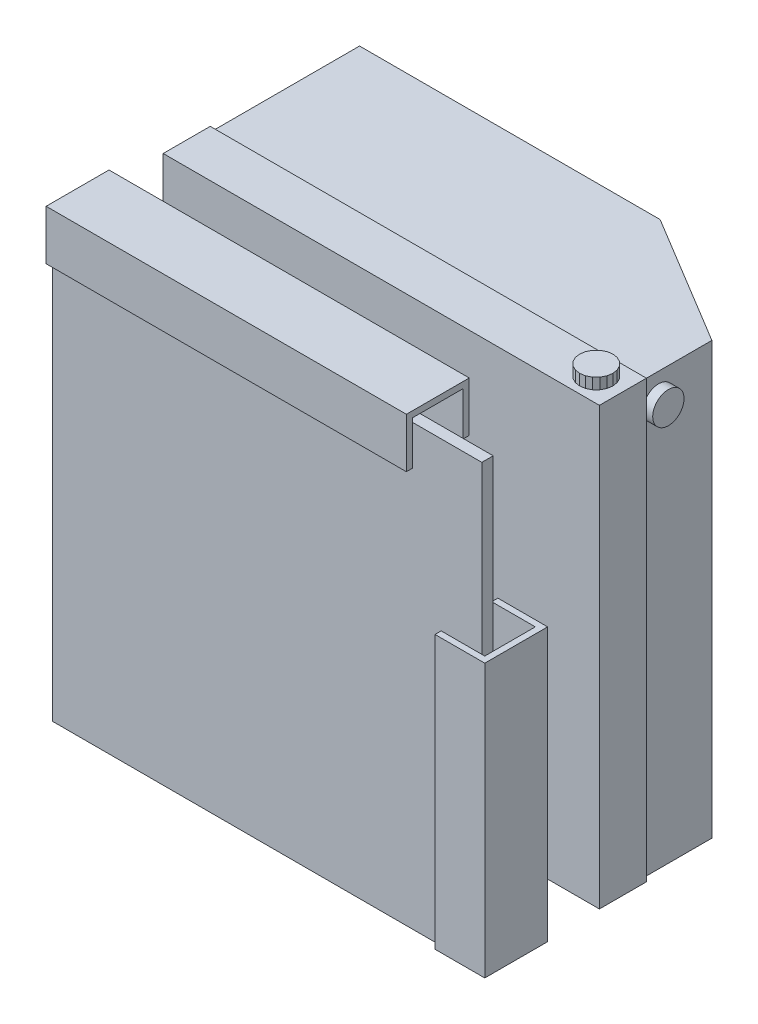
SolidWorks part; units mm, degrees
ref_plane "Front Plane" through (0, 0, 0) normal (0, 0, 1) x (1, 0, 0)
ref_plane "Top Plane" through (0, 0, 0) normal (0, 1, 0) x (1, 0, 0)
ref_plane "Right Plane" through (0, 0, 0) normal (1, 0, 0) x (0, 0, -1)
ref_plane "PY -55.000" through (0, -55, 0) normal (0, 1, 0) x (1, 0, 0)
sketch "housing sketch" plane through (0, -55, 0) normal (0, 1, 0) x (1, 0, 0)
  line L0 (0, 0) -> (0, 30)
  line L1 (0, 30) -> (-33.3047, 50.1)
  line L2 (-33.3047, 50.1) -> (-110, 50.1)
  line L3 (-110, 50.1) -> (-110, 0)
  line L4 (-110, 0) -> (0, 0)
extrude "housing" add sketch "housing sketch" along normal mid plane 110
ref_plane "PZ 26.850" through (0, 0, 26.85) normal (0, 0, 1) x (1, 0, 0)
sketch "diffuser sketch" plane through (0, 0, 26.85) normal (0, 0, 1) x (1, 0, 0)
  line L0 (-110, -110) -> (-0.4, -110)
  line L1 (-0.4, -110) -> (-0.4, 2)
  line L2 (-0.4, 2) -> (-110, 2)
  line L3 (-110, 2) -> (-110, -110)
extrude "diffuser" add sketch "diffuser sketch" along normal mid plane 2.9
ref_plane "PY -75.215" through (0, -75.215, 0) normal (0, 1, 0) x (1, 0, 0)
sketch "side channel sketch" plane through (0, -75.215, 0) normal (0, 1, 0) x (1, 0, 0)
  line L0 (-10.78, -13.83) -> (1.92, -13.83)
  line L1 (1.92, -13.83) -> (1.92, -29.87)
  line L2 (1.92, -29.87) -> (-10.78, -29.87)
  line L3 (-10.78, -29.87) -> (-10.78, -28.3)
  line L4 (-10.78, -28.3) -> (0.35, -28.3)
  line L5 (0.35, -28.3) -> (0.35, -15.4)
  line L6 (0.35, -15.4) -> (-10.78, -15.4)
  line L7 (-10.78, -15.4) -> (-10.78, -13.83)
extrude "side channel" add sketch "side channel sketch" along normal mid plane 69.57
ref_plane "PX -64.040" through (-64.04, 0, 0) normal (1, 0, 0) x (0, 0, -1)
sketch "end channel sketch" plane through (-64.04, 0, 0) normal (1, 0, 0) x (0, 0, -1)
  line L0 (-13.83, -8.13) -> (-13.83, 4.57)
  line L1 (-13.83, 4.57) -> (-29.87, 4.57)
  line L2 (-29.87, 4.57) -> (-29.87, -8.13)
  line L3 (-29.87, -8.13) -> (-28.3, -8.13)
  line L4 (-28.3, -8.13) -> (-28.3, 3)
  line L5 (-28.3, 3) -> (-15.4, 3)
  line L6 (-15.4, 3) -> (-15.4, -8.13)
  line L7 (-15.4, -8.13) -> (-13.83, -8.13)
extrude "end channel" add sketch "end channel sketch" along normal mid plane 91.92
ref_plane "PX 0.750" through (0.75, 0, 0) normal (1, 0, 0) x (0, 0, -1)
sketch "side screw head sketch" plane through (0.75, 0, 0) normal (1, 0, 0) x (0, 0, -1)
  circle A0 centre (16.4, -6.8) radius 4
extrude "side screw head" add sketch "side screw head sketch" along normal mid plane 3.5
ref_plane "PY -54.350" through (0, -54.35, 0) normal (0, 1, 0) x (1, 0, 0)
sketch "lens frame lap sketch" plane through (0, -54.35, 0) normal (0, 1, 0) x (1, 0, 0)
  line L0 (-110, 12) -> (1.3, 12)
  line L1 (1.3, 12) -> (1.3, 0)
  line L2 (1.3, 0) -> (-110, 0)
  line L3 (-110, 0) -> (-110, 12)
extrude "lens frame lap" add sketch "lens frame lap sketch" along normal mid plane 111.3
ref_plane "PY 1.550" through (0, 1.55, 0) normal (0, 1, 0) x (1, 0, 0)
sketch "corner screw head on the end sketch" plane through (0, 1.55, 0) normal (0, 1, 0) x (1, 0, 0)
  line L0 (-1.25, 6) -> (-1.458, 4.6867)
  line L1 (-1.458, 4.6867) -> (-2.0617, 3.5019)
  line L2 (-2.0617, 3.5019) -> (-3.0019, 2.5617)
  line L3 (-3.0019, 2.5617) -> (-4.1867, 1.958)
  line L4 (-4.1867, 1.958) -> (-5.5, 1.75)
  line L5 (-5.5, 1.75) -> (-6.8133, 1.958)
  line L6 (-6.8133, 1.958) -> (-7.9981, 2.5617)
  line L7 (-7.9981, 2.5617) -> (-8.9383, 3.5019)
  line L8 (-8.9383, 3.5019) -> (-9.542, 4.6867)
  line L9 (-9.542, 4.6867) -> (-9.75, 6)
  line L10 (-9.75, 6) -> (-9.542, 7.3133)
  line L11 (-9.542, 7.3133) -> (-8.9383, 8.4981)
  line L12 (-8.9383, 8.4981) -> (-7.9981, 9.4383)
  line L13 (-7.9981, 9.4383) -> (-6.8133, 10.042)
  line L14 (-6.8133, 10.042) -> (-5.5, 10.25)
  line L15 (-5.5, 10.25) -> (-4.1867, 10.042)
  line L16 (-4.1867, 10.042) -> (-3.0019, 9.4383)
  line L17 (-3.0019, 9.4383) -> (-2.0617, 8.4981)
  line L18 (-2.0617, 8.4981) -> (-1.458, 7.3133)
  line L19 (-1.458, 7.3133) -> (-1.25, 6)
extrude "corner screw head on the end" add sketch "corner screw head on the end sketch" along normal mid plane 5.1
ref_plane "PY -20.700" through (0, -20.7, 0) normal (0, 1, 0) x (1, 0, 0)
sketch "insert flange sketch" plane through (0, -20.7, 0) normal (0, 1, 0) x (1, 0, 0)
  line L0 (-18.3249, 39.8914) -> (-17.2914, 41.6037)
  line L1 (-17.2914, 41.6037) -> (-12.026, 38.426)
  line L2 (-12.026, 38.426) -> (-13.0595, 36.7136)
  line L3 (-13.0595, 36.7136) -> (-18.3249, 39.8914)
revolve "insert flange" add sketch "insert flange sketch" angle 360 about L0
equation "\"diffL\"= 608.8mm"
equation "\"diffW\"= 329.4mm"
equation "\"diffT\"= 2.9mm"
equation "\"chanSlotW\"= 12.9mm"
equation "\"chanSlotDepth\"= 11.13mm"
equation "\"chanFloor\"= 1.57mm"
equation "\"chanLeg\"= 12.7mm"
equation "\"lightL\"= 605mm"
equation "\"lightW\"= 331mm"
equation "\"lightH\"= 92mm"
equation "\"lightSideFlat\"= 30mm"
equation "\"lightSlopeLen\"= 33.1mm"
equation "\"lightWingDepth\"= 47.9mm"
equation "\"lightWingFlat\"= 90.2mm"
equation "\"lightChanW\"= 99.6mm"
equation "\"lightChanStand\"= 44.1mm"
equation "\"insFlangeD\"= 12.3mm"
equation "\"insFromEnd\"= 20.7mm"
equation "\"insUpSlope\"= 20.8mm"
equation "\"gaugeH\"= 10mm"
equation "\"gaugeStepLen\"= 14mm"
equation "\"gaugeStepW0\"= 13.1mm"
equation "\"gaugeStepDW\"= 0.2mm"
equation "\"gaugeSteps\"= 5mm"
equation "\"gaugeHandleLen\"= 30mm"
equation "\"gaugeHandleW\"= 24mm"
equation "\"gaugeSlot0\"= 3mm"
equation "\"gaugeSlotD\"= 0.1mm"
equation "\"gaugeSlotDepth\"= 8mm"
equation "\"gap\"= 25.4mm"
equation "\"edgeL\"= 1mm"
equation "\"edgeW\"= 0.75mm"
equation "\"proud\"= 1.5mm"
equation "\"seatClr\"= 0.15mm"
equation "\"tongueClrZ\"= 0.1mm"
equation "\"tongueClrX\"= 0.25mm"
equation "\"tongueLen\"= 30mm"
equation "\"armSide\"= 45mm"
equation "\"armEnd\"= 20mm"
equation "\"cornerCham\"= 3mm"
equation "\"brkW\"= 26mm"
equation "\"brkT\"= 7mm"
equation "\"brkSeatClr\"= 0.2mm"
equation "\"brkScrewSpan\"= 16mm"
equation "\"pilotD\"= 2.7mm"
equation "\"pilotDepth\"= 10mm"
equation "\"screwClrD\"= 3.9mm"
equation "\"jogBelow\"= 4mm"
equation "\"padT\"= 7mm"
equation "\"padLen\"= 31mm"
equation "\"m6Clr\"= 7mm"
equation "\"m6Slot\"= 3mm"
equation "\"flangeRelD\"= 17mm"
equation "\"flangeRelDepth\"= 1.5mm"
equation "\"relLen\"= 7mm"
equation "\"relDepth\"= 4mm"
equation "\"relLand\"= 2mm"
equation "\"knockN\"= 100mm"
equation "\"petgcfE\"= 3000mm"
equation "\"mockExtent\"= 110mm"
equation "\"relZnear\"= 9.4mm"
equation "\"relZfar\"= 23.4mm"
equation "\"headD\"= 8mm"
equation "\"headH\"= 2.5mm"
equation "\"headFromEnd\"= 6.8mm"
equation "\"headBack\"= 16.4mm"
equation "\"sideClr\"= 0.4mm"
equation "\"cornerRelR\"= 1.5mm"
equation "\"cornerRelBack\"= 0.6mm"
equation "\"endHeadH\"= 2.8mm"
equation "\"footClr\"= 1.2mm"
equation "\"footEndClr\"= 3.5mm"
equation "\"footLift\"= 6mm"
equation "\"footBlockClr\"= 0.5mm"
equation "\"footBack\"= 50mm"
equation "\"footFwd\"= 10mm"
equation "\"footBraceEnd\"= 3mm"
equation "\"footLoadN\"= 25mm"
equation "\"spacerLen\"= 60mm"
equation "\"spacerShort\"= 0.5mm"
equation "\"spacerCham\"= 0.8mm"
equation "\"spacerPerSide\"= 3mm"
equation "\"spacerPerEnd\"= 1mm"
equation "\"toolR\"= 9mm"
equation "\"visR\"= 4mm"
equation "\"edgeR\"= 1mm"
equation "\"bendOutR\"= 5mm"
equation "\"insideR\"= 2.5mm"
equation "\"footCornerR\"= 10mm"
equation "\"footFrontR\"= 8mm"
equation "\"braceKinkR\"= 12mm"
equation "\"bedCham\"= 1mm"
equation "\"bedChamSmall\"= 0.6mm"
equation "\"soleTopR\"= 2mm"
equation "\"cornerR\"= 6mm"
equation "\"rimInR\"= 1mm"
equation "\"insFlangeH\"= 1mm"
equation "\"insHoleFinishD\" = 4.5mm"
equation "\"insLen\" = 6.4mm"
equation "\"cgInset\" = 4mm"
equation "\"lampWeightN\" = 51mm"
equation "\"frameWeightN\" = 10mm"
equation "\"bumpIn\" = 8mm"
equation "\"bumpH\" = 3mm"
equation "\"legBelowFront\" = 2mm"
equation "\"lipClr\" = 0.1mm"
equation "\"revealR\" = 2mm"
equation "\"frontCham\" = 1mm"
equation "\"leanDeg\" = 5mm"
equation "\"footTailT\" = 6mm"
equation "\"v1LeanDeg\" = 4.5mm"
equation "\"toeNoseR\" = 5mm"
equation "\"petgE\" = 2000mm"
equation "\"cheekT\" = 8mm"
equation "\"handleUp\" = 50mm"
equation "\"handleZ\" = -10mm"
equation "\"gripD\" = 19.05mm"
equation "\"gripClr\" = 0.5mm"
equation "\"bossWall\" = 5mm"
equation "\"bossLen\" = 14mm"
equation "\"socketFloor\" = 4mm"
equation "\"barEndClr\" = 1mm"
equation "\"lipH\" = 4mm"
equation "\"lipDeep\" = 6mm"
equation "\"stripT\" = 1.3mm"
equation "\"stripW\" = 12mm"
equation "\"stripClr\" = 0.5mm"
equation "\"stripBack\" = 3mm"
equation "\"endRelClr\" = 1mm"
equation "\"cornerScrewX\" = 5.5mm"
equation "\"cornerScrewZ\" = 6mm"
equation "\"cornerScrewD\" = 8.5mm"
equation "\"footTabIn\" = 33mm"
equation "\"footTabZ1\" = 50mm"
equation "\"footTabZ2\" = 19mm"
equation "\"footTabR\" = 8mm"
equation "\"landAx0\" = -17mm"
equation "\"landAz0\" = -30mm"
equation "\"landAx1\" = -3mm"
equation "\"landAz1\" = -18mm"
equation "\"landBx0\" = -60mm"
equation "\"landBz0\" = -43mm"
equation "\"landBx1\" = -46mm"
equation "\"landBz1\" = -27mm"
